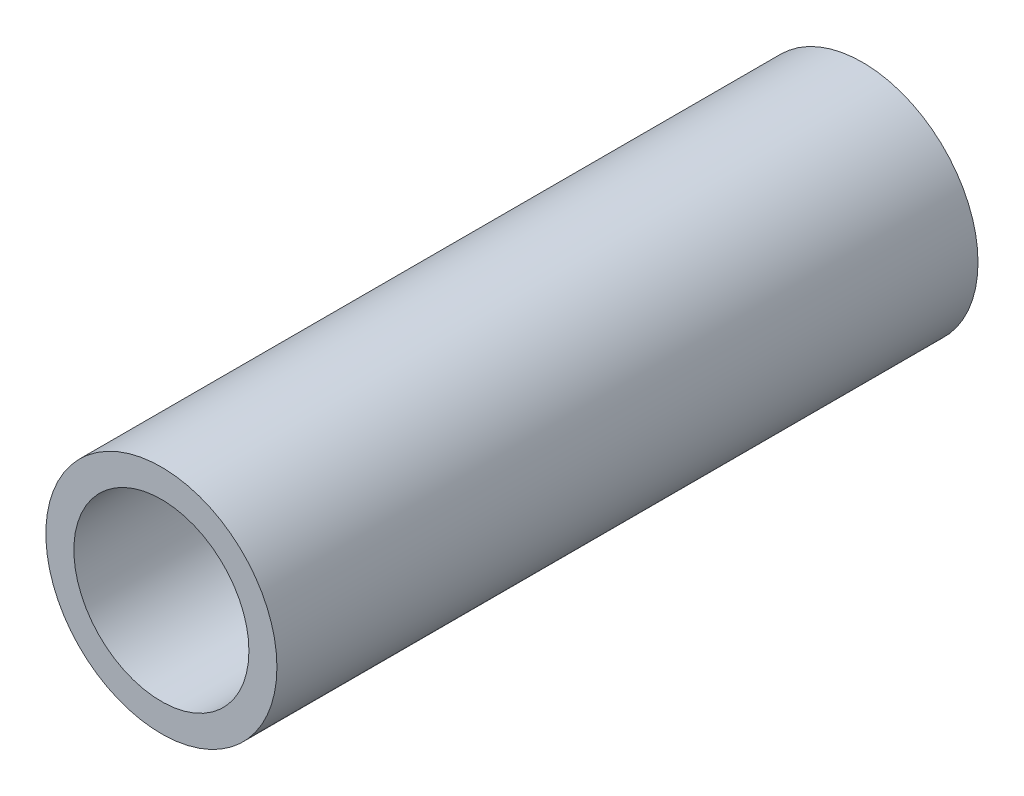
SolidWorks part; units mm, degrees
material "AISI 304"
ref_plane "前基準面" through (0, 0, 0) normal (0, 0, 1) x (1, 0, 0)
ref_plane "上基準面" through (0, 0, 0) normal (0, 1, 0) x (1, 0, 0)
ref_plane "右基準面" through (0, 0, 0) normal (1, 0, 0) x (0, 0, -1)
sketch "Sketch1" plane through (0, 0, 0) normal (0, 0, 1) x (1, 0, 0)
  circle A0 centre (0, 0) radius 14.6685
  circle A1 centre (0, 0) radius 11.1125
  dimension "D1" = 22.225
  dimension "D2" = 29.337
extrude "Boss-Extrude1" add sketch "Sketch1" along normal mid plane 89
